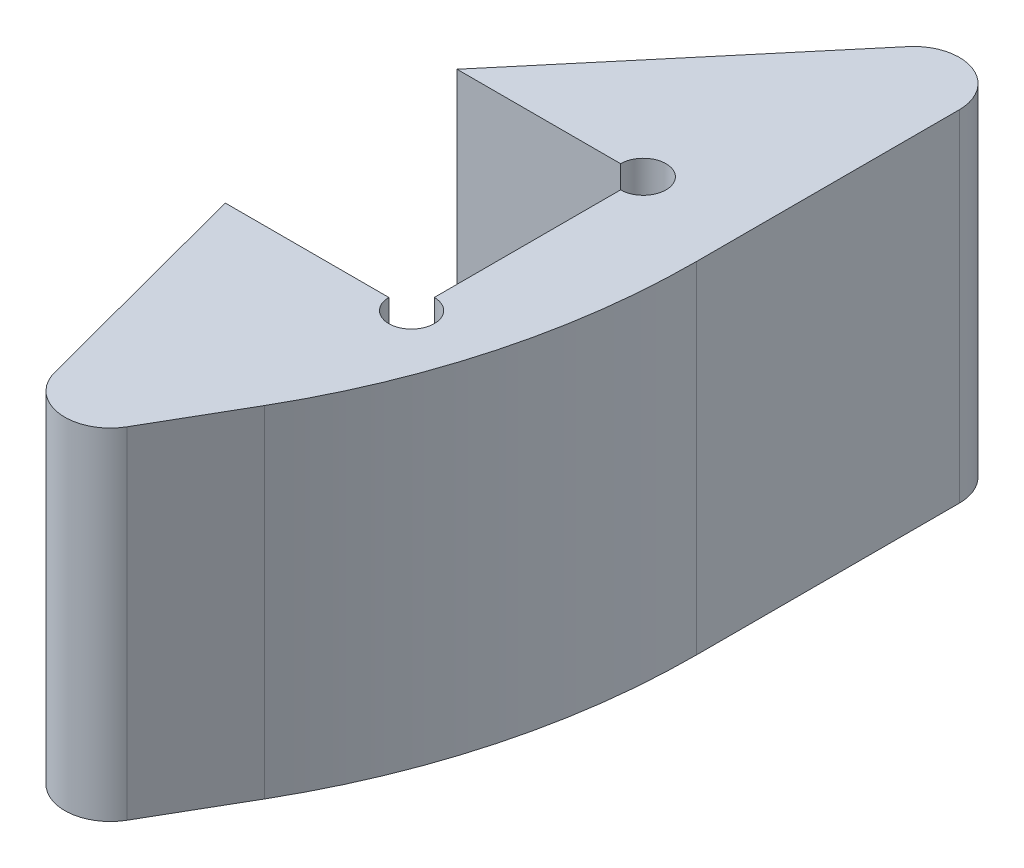
SolidWorks part; units mm, degrees
material "ﾎﾟﾘｴｽﾃﾙ樹脂"
ref_plane "正面" through (0, 0, 0) normal (0, 0, 1) x (1, 0, 0)
ref_plane "平面" through (0, 0, 0) normal (0, 1, 0) x (1, 0, 0)
ref_plane "右側面" through (0, 0, 0) normal (1, 0, 0) x (0, 0, -1)
sketch "ｽｹｯﾁ1" plane through (0, 0, 0) normal (0, 1, 0) x (1, 0, 0)
  line L0 (-4.1, 5.1) -> (8.5, 20.1)
  line L1 (-4, -5) -> (4, -5) construction
  line L2 (-4, -5) -> (-4, 5) construction
  line L3 (-4, 5) -> (4, 5) construction
  line L4 (4, -5) -> (4, 5) construction
  line L5 (-4, -5) -> (4, 5) construction
  line L6 (-4, 5) -> (4, -5) construction
  line L7 (-4.1, -5.1) -> (4.1, -5.1)
  line L8 (-4.1, -5.1) -> (-4.1, 5.1)
  line L9 (-4.1, 5.1) -> (4.1, 5.1)
  line L10 (4.1, -5.1) -> (4.1, 5.1)
  line L11 (-4.1, -5.1) -> (4.1, 5.1) construction
  line L12 (-4.1, 5.1) -> (4.1, -5.1) construction
  line L13 (8.5, 20.1) -> (8.5, -5)
  line L14 (8.5, -5) -> (-0.1603, -20)
  line L15 (-0.1603, -20) -> (-4.1, -5.1)
  line L16 (4, -5) -> (8.5, -5) construction
  circle A0 centre (0, 0) radius 1.75
  point P0 (0, 0)
  dimension "D3" = 3.5
  dimension "D1" = 10
  dimension "D2" = 8
  dimension "D4" = 10.2
  dimension "D5" = 8.2
  dimension "D6" = 4.5
  dimension "D7" = 15
  dimension "D8" = 15
  dimension "D9" = 30
extrude "ﾎﾞｽ - 押し出し1" add sketch "ｽｹｯﾁ1" along normal blind 15 contours L15 L14 L13 L0 L9 L10 L7 | L7 L10 L9 L8 A0
sketch "ｽｹｯﾁ2" plane through (0, 15, 0) normal (0, 1, 0) x (1, 0, 0)
  line L1 (4.1, -5.1) -> (-4.1, -5.1)
  line L2 (4.1, -5.1) -> (4.1, 5.1)
  line L3 (4.1, 5.1) -> (-4.1, 5.1)
  line L4 (-4.1, -5.1) -> (-4.1, 5.1)
  line L5 (4.1, -5.1) -> (-4.1, 5.1) construction
  line L6 (4.1, 5.1) -> (-4.1, -5.1) construction
  point P0 (0, 0)
extrude "ｶｯﾄ - 押し出し1" cut sketch "ｽｹｯﾁ2" against normal blind 10
sketch "ｽｹｯﾁ4" plane through (0, 15, 0) normal (0, 1, 0) x (1, 0, 0)
  circle A0 centre (4.1, 5.1) radius 1
  circle A1 centre (4.1, -5.1) radius 1
  dimension "D1" = 2
  dimension "D2" = 2
extrude "ｶｯﾄ - 押し出し2" cut sketch "ｽｹｯﾁ4" against normal up to surface (10 mm away) up to face at (0, 5, 1.75)
fillet "ﾌｨﾚｯﾄ1" radius 30 1 edges at (8.5, 7.5, 5)
fillet "ﾌｨﾚｯﾄ2" radius 2 2 edges at (8.5, 7.5, -20.1) (-0.1603, 7.5, 20)
